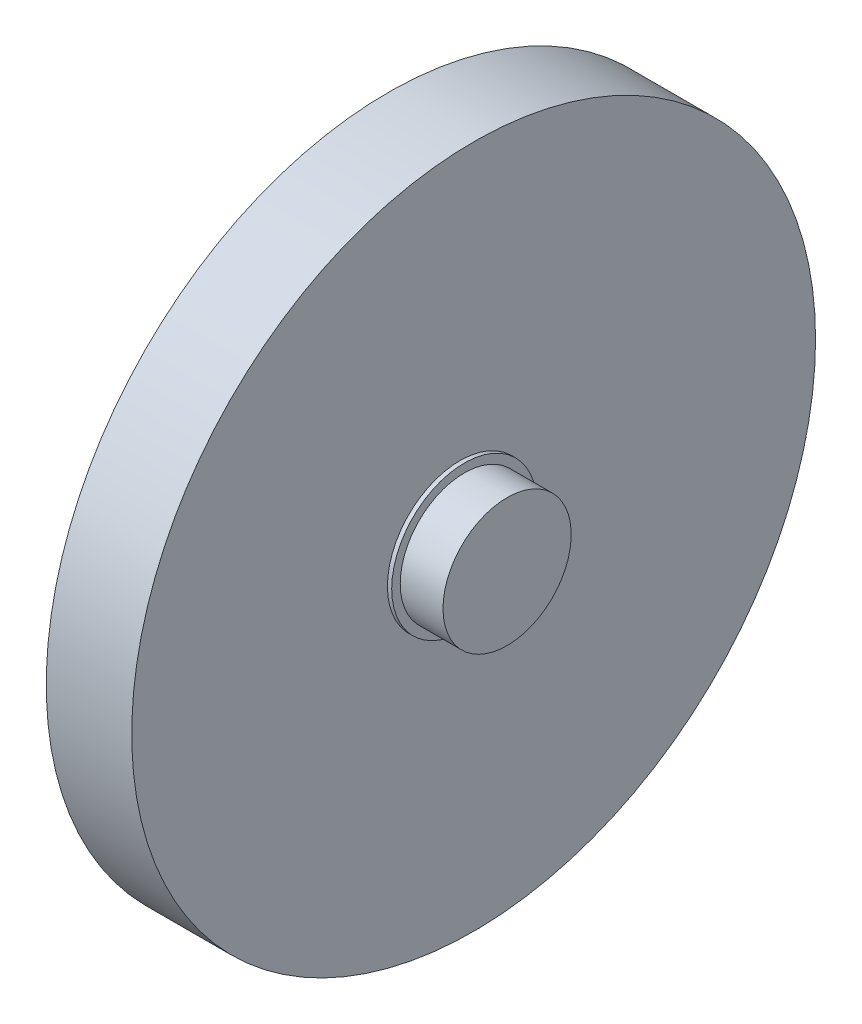
SolidWorks part; units mm, degrees
ref_plane "Front Plane" through (0, 0, 0) normal (0, 0, 1) x (1, 0, 0)
ref_plane "Top Plane" through (0, 0, 0) normal (0, 1, 0) x (1, 0, 0)
ref_plane "Right Plane" through (0, 0, 0) normal (1, 0, 0) x (0, 0, -1)
sketch "Sketch1" plane through (0, 0, 0) normal (1, 0, 0) x (0, 0, -1)
  circle A0 centre (0, 0) radius 31.75 construction
  circle A1 centre (0, 31.75) radius 3.175
  circle A2 centre (18.6622, 25.6863) radius 3.175
  circle A3 centre (30.196, 9.8113) radius 3.175
  circle A4 centre (30.196, -9.8113) radius 3.175
  circle A5 centre (18.6622, -25.6863) radius 3.175
  circle A6 centre (0, -31.75) radius 3.175
  circle A7 centre (-18.6622, -25.6863) radius 3.175
  circle A8 centre (-30.196, -9.8113) radius 3.175
  circle A9 centre (-30.196, 9.8113) radius 3.175
  circle A10 centre (-18.6622, 25.6863) radius 3.175
  arc A11 (15.5029, 26.0022) -> (2.7416, 30.1486) centre (8.6706, 26.6853) ccw
  circle A12 centre (0, 0) radius 34.925 construction
  arc A13 (27.8258, 11.9238) -> (19.9389, 22.7793) centre (22.6999, 16.4924) ccw
  arc A14 (29.5202, -6.7091) -> (29.5202, 6.7091) centre (28.0586, 0) ccw
  arc A15 (19.9389, -22.7793) -> (27.8258, -11.9238) centre (22.6999, -16.4924) ccw
  arc A16 (2.7416, -30.1486) -> (15.5029, -26.0022) centre (8.6706, -26.6853) ccw
  arc A17 (-15.5029, -26.0022) -> (-2.7416, -30.1486) centre (-8.6706, -26.6853) ccw
  arc A18 (-27.8258, -11.9238) -> (-19.9389, -22.7793) centre (-22.6999, -16.4924) ccw
  arc A19 (-29.5202, 6.7091) -> (-29.5202, -6.7091) centre (-28.0586, 0) ccw
  arc A20 (-19.9389, 22.7793) -> (-27.8258, 11.9238) centre (-22.6999, 16.4924) ccw
  arc A21 (-2.7416, 30.1486) -> (-15.5029, 26.0022) centre (-8.6706, 26.6853) ccw
  circle A23 centre (1.5875, 0) radius 40
  point P26 (0, 0)
  point P58 (0, 0)
  point P59 (0, 0)
  dimension "D1" = 63.5
  dimension "D2" = 6.35
  dimension "D7" = 80
  dimension "D6" = 1.5875
  dimension "D3" = 10
  dimension "D4" = 10
extrude "Boss-Extrude1" add sketch "Sketch1" along normal blind 7 contours A23 A21 A1 A11 A2 A13 A3 A14 A4 A15 A5 A16 A6 A17 A7 A18 A8 A19 A9 A20 A10 | A2 | A3 | A4 | A5 | A6 | A7 | A8 | A9 | A10 | A1
sketch "Sketch2" plane through (7, 0, 0) normal (1, 0, 0) x (0, 0, -1)
  circle A0 centre (1.5875, 0) radius 40 construction
  circle A1 centre (1.5875, 0) radius 40
  circle A2 centre (0, 0) radius 4
  point P5 (-2.4943, -0.7171)
  point P6 (0, 0)
  dimension "D1" = 8
extrude "Boss-Extrude2" add sketch "Sketch2" along normal blind 2.5
sketch "Sketch3" plane through (9.5, 0, 0) normal (1, 0, 0) x (0, 0, -1)
  circle A0 centre (0, 0) radius 3.75
  circle M1 centre (1.5875, 0) radius 40
  circle M2 centre (0, 0) radius 4
  dimension "D1" = 7.5
extrude "Boss-Extrude3" add sketch "Sketch3" along normal blind 0.5 contours M1 M2 | A0 M2
sketch "Sketch4" plane through (0, 0, 0) normal (0, 0, 1) x (1, 0, 0)
  line L0 (10, 0) -> (28.1668, 0) construction
  line L1 (10, 8.5) -> (10.5, 8.5)
  line L2 (10.5, 8.5) -> (10.5, 7.5)
  line L3 (10.5, 7.5) -> (15.5, 7.5)
  line L4 (15.5, 7.5) -> (15.5, 0)
  line L5 (10, -40) -> (10, 40) construction
  line L6 (10, 8.5) -> (10, 3.75)
  line L7 (10, 0) -> (15.5, 0) construction
  line L8 (10, 3.75) -> (12.325, 3.75)
  line L9 (12.325, 3.75) -> (12.325, 0)
  line L10 (12.325, 0) -> (15.5, 0)
  dimension "D1" = 5
  dimension "D2" = 0.5
  dimension "D3" = 1
  dimension "D4" = 7.5
  dimension "D5" = 3.75
  dimension "D6" = 3.175
revolve "Revolve1" add sketch "Sketch4" angle 360 about L10
